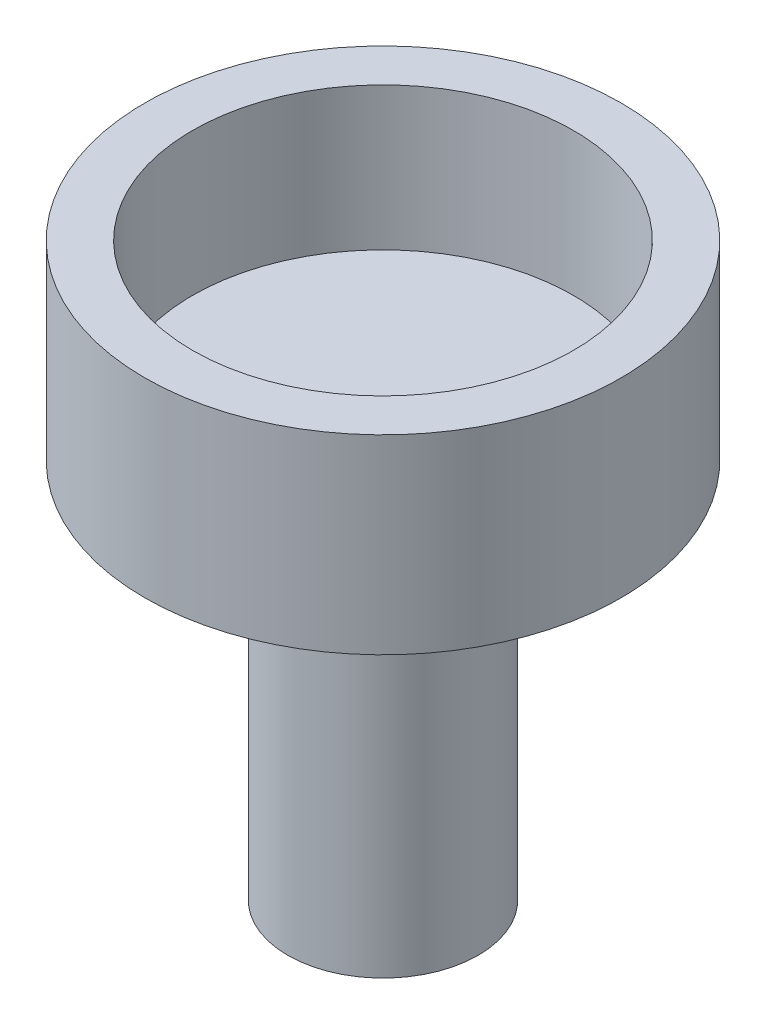
SolidWorks part; units mm, degrees
material "Natural Rubber"
ref_plane "Front Plane" through (0, 0, 0) normal (0, 0, 1) x (1, 0, 0)
ref_plane "Top Plane" through (0, 0, 0) normal (0, 1, 0) x (1, 0, 0)
ref_plane "Right Plane" through (0, 0, 0) normal (1, 0, 0) x (0, 0, -1)
sketch "BottomBaseS" plane through (0, 0, 0) normal (0, 1, 0) x (1, 0, 0)
  circle A0 centre (0, 0) radius 1
  dimension "Dia" = 2
extrude "BOTTOM BASE" add sketch "BottomBaseS" against normal blind 4
sketch "MainBaseS" plane through (0, 0, 0) normal (0, 1, 0) x (1, 0, 0)
  circle A0 centre (0, 0) radius 2.5
  circle A1 centre (0, 0) radius 1 construction
  dimension "RefDiaBase" = 5
  dimension "BaseDiaControl" = 1.5
extrude "MAIN BASE" add sketch "MainBaseS" along normal blind 0.5
sketch "WallS" plane through (0, 0.5, 0) normal (0, 1, 0) x (1, 0, 0)
  circle A0 centre (0, 0) radius 2.5
  circle A1 centre (0, 0) radius 2
  circle A2 centre (0, 0) radius 2.5 construction
  dimension "Thickness" = 0.5
extrude "WALL" add sketch "WallS" along normal offset from surface (1.5 mm away) 2 up to face at (0, 0, 1)
